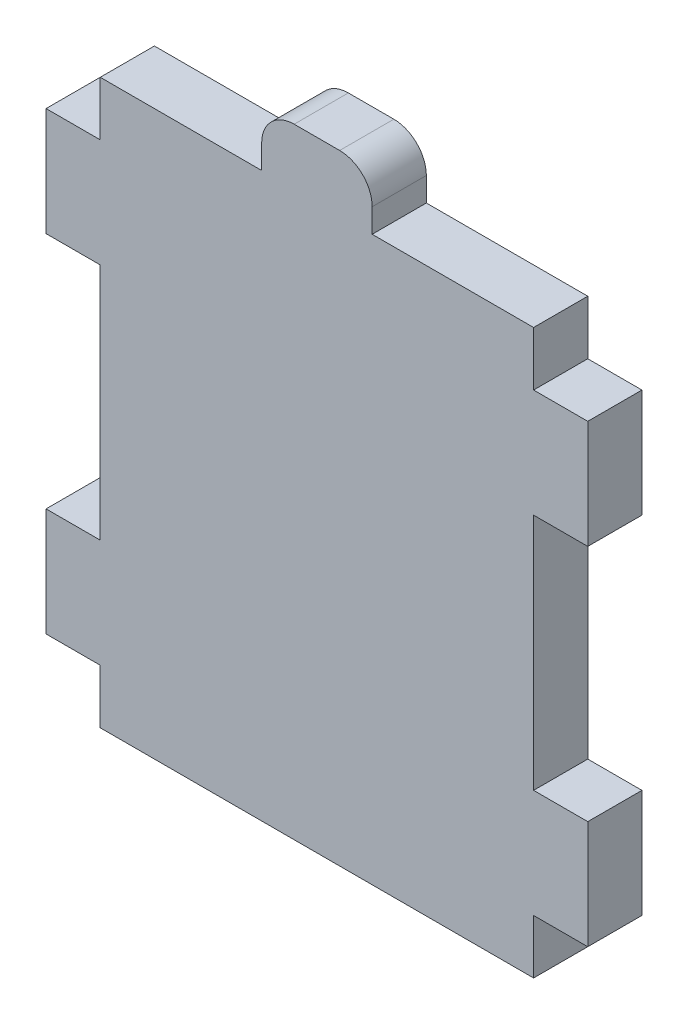
SolidWorks part; units mm, degrees
ref_plane "Front Plane" through (0, 0, 0) normal (0, 0, 1) x (1, 0, 0)
ref_plane "Top Plane" through (0, 0, 0) normal (0, 1, 0) x (1, 0, 0)
ref_plane "Right Plane" through (0, 0, 0) normal (1, 0, 0) x (0, 0, -1)
sketch "Sketch1" plane through (0, 0, 0) normal (0, 0, 1) x (1, 0, 0)
  line L1 (0, 0) -> (50.8, 0)
  line L2 (0, 0) -> (0, 66.04)
  line L3 (0, 66.04) -> (50.8, 66.04)
  line L4 (50.8, 0) -> (50.8, 66.04)
  dimension "D1" = 66.04
  dimension "D2" = 50.8
extrude "Boss-Extrude1" add sketch "Sketch1" along normal blind 6.35
sketch "Sketch2" plane through (0, 0, 0) normal (0, 0, 1) x (1, 0, 0)
  line L0 (0, 66.04) -> (0, 0) construction
  line L1 (0, 59.69) -> (-6.35, 59.69)
  line L2 (0, 59.69) -> (0, 46.99)
  line L3 (0, 46.99) -> (-6.35, 46.99)
  line L4 (-6.35, 59.69) -> (-6.35, 46.99)
  line L5 (50.8, 66.04) -> (0, 66.04) construction
  line L6 (25.4, 66.04) -> (25.4, 0) construction
  line L7 (0, 0) -> (50.8, 0) construction
  line L8 (0, 33.02) -> (50.8, 33.02) construction
  line L9 (50.8, 0) -> (50.8, 66.04) construction
  line L10 (0, 19.05) -> (-6.35, 19.05)
  line L11 (-6.35, 6.35) -> (-6.35, 19.05)
  line L12 (0, 6.35) -> (-6.35, 6.35)
  line L13 (0, 6.35) -> (0, 19.05)
  line L14 (50.8, 6.35) -> (50.8, 19.05)
  line L15 (50.8, 6.35) -> (57.15, 6.35)
  line L16 (57.15, 6.35) -> (57.15, 19.05)
  line L17 (50.8, 19.05) -> (57.15, 19.05)
  line L18 (50.8, 46.99) -> (57.15, 46.99)
  line L19 (57.15, 59.69) -> (57.15, 46.99)
  line L20 (50.8, 59.69) -> (57.15, 59.69)
  line L21 (50.8, 59.69) -> (50.8, 46.99)
  line L23 (18.923, 66.04) -> (31.877, 66.04)
  line L24 (18.923, 66.04) -> (18.923, 68.834)
  line L25 (22.733, 72.644) -> (28.067, 72.644)
  line L26 (31.877, 66.04) -> (31.877, 68.834)
  arc A0 (28.067, 72.644) -> (31.877, 68.834) centre (28.067, 68.834) cw
  arc A1 (18.923, 68.834) -> (22.733, 72.644) centre (22.733, 68.834) cw
  point P32 (25.4, 66.04)
  point P35 (31.877, 72.644)
  point P38 (18.923, 72.644)
  dimension "D6" = 3.81
  dimension "D1" = 6.35
  dimension "D2" = 12.7
  dimension "D3" = 6.35
  dimension "D4" = 12.954
  dimension "D5" = 6.604
extrude "Boss-Extrude2" add sketch "Sketch2" along normal blind 6.35
